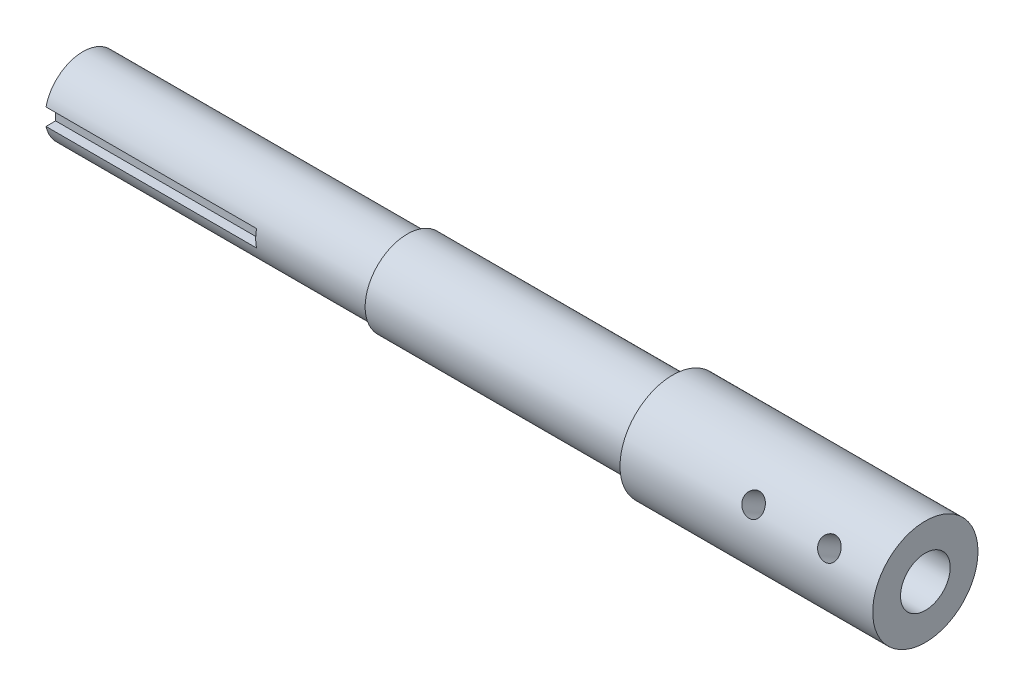
SolidWorks part; units mm, degrees
ref_plane "Front Plane" through (0, 0, 0) normal (0, 0, 1) x (1, 0, 0)
ref_plane "Top Plane" through (0, 0, 0) normal (0, 1, 0) x (1, 0, 0)
ref_plane "Right Plane" through (0, 0, 0) normal (1, 0, 0) x (0, 0, -1)
sketch "Sketch2" plane through (0, 0, 0) normal (1, 0, 0) x (0, 0, -1)
  circle A0 centre (0, 0) radius 10
  dimension "D1" = 20
extrude "Boss-Extrude1" add sketch "Sketch2" along normal blind 63
sketch "Sketch3" plane through (63, 0, 0) normal (1, 0, 0) x (0, 0, -1)
  circle A0 centre (0, 0) radius 12.5
  dimension "D1" = 25
extrude "Boss-Extrude2" add sketch "Sketch3" along normal blind 60
sketch "Sketch5" plane through (123, 0, 0) normal (1, 0, 0) x (0, 0, -1)
  circle A0 centre (0, 0) radius 5.9
  dimension "D1" = 11.8
extrude "Cut-Extrude1" cut sketch "Sketch5" against normal blind 40
sketch "Sketch6" plane through (0, 0, 0) normal (0, 1, 0) x (1, 0, 0)
  line L0 (123, -12.5) -> (123, 12.5) construction
  circle A0 centre (93, 0) radius 2.5
  circle A1 centre (111, 0) radius 2.5
  dimension "D2" = 30
  dimension "D4" = 5
  dimension "D1" = 12
extrude "Cut-Extrude2" cut sketch "Sketch6" against normal blind 55
pattern_circular "CirPattern1" count 3 over 360 about axis through (123, 0, 0) along (1, 0, 0) of "Cut-Extrude2"
sketch "Sketch8" plane through (0, 0, 0) normal (-1, 0, 0) x (0, 0, 1)
  circle A0 centre (0, 0) radius 9
extrude "Boss-Extrude3" add sketch "Sketch8" along normal blind 77 contours A0
sketch "Sketch9" plane through (-77, 0, 0) normal (-1, 0, 0) x (0, 0, 1)
  line L0 (9, 0) -> (6.5, 0) construction
  line L1 (6.5, 2) -> (6.5, -2)
  line L2 (6.5, -2) -> (10.3836, -2)
  line L3 (10.3836, -2) -> (10.3836, 2)
  line L4 (10.3836, 2) -> (6.5, 2)
  circle A0 centre (0, 0) radius 9 construction
  circle A1 centre (0, 0) radius 9 construction
  dimension "D1" = 2.5
  dimension "D2" = 4
extrude "Cut-Extrude3" cut sketch "Sketch9" against normal blind 50
